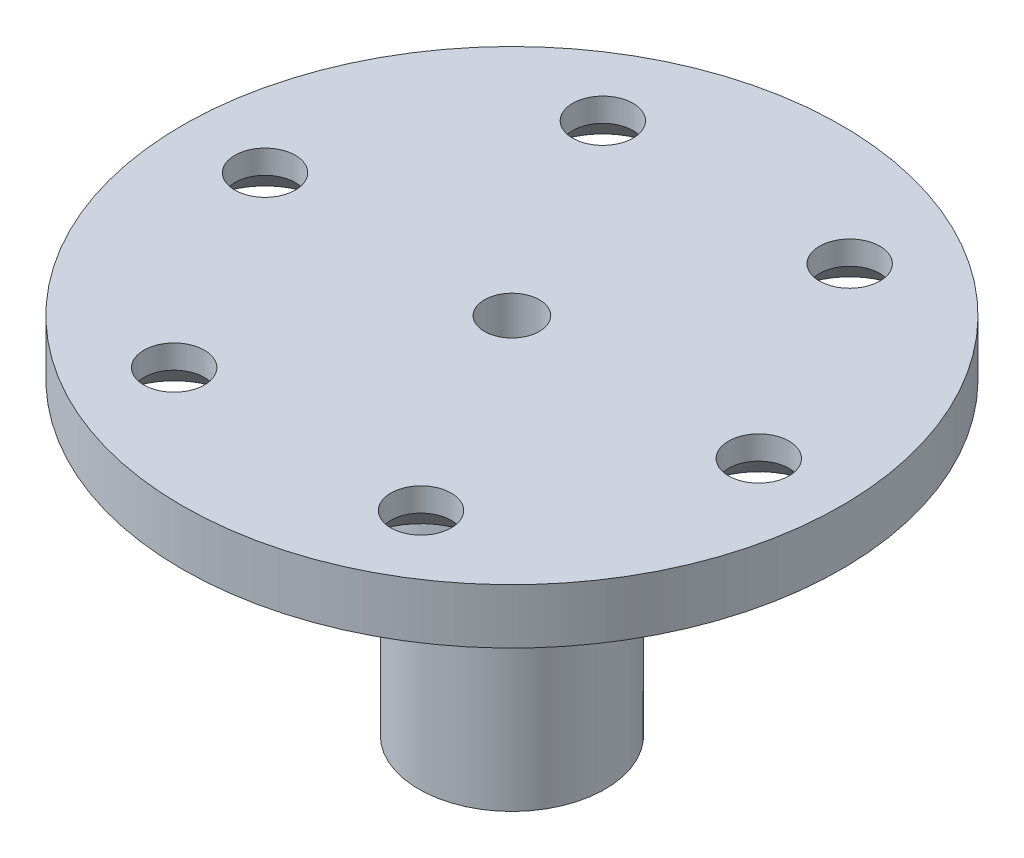
SolidWorks part; units mm, degrees
ref_plane "前视基准面" through (0, 0, 0) normal (0, 0, 1) x (1, 0, 0)
ref_plane "上视基准面" through (0, 0, 0) normal (0, 1, 0) x (1, 0, 0)
ref_plane "右视基准面" through (0, 0, 0) normal (1, 0, 0) x (0, 0, -1)
sketch "草图1" plane through (0, 0, 0) normal (0, 1, 0) x (1, 0, 0)
  circle A0 centre (0, 0) radius 8.475
  dimension "D1" = 16.95
extrude "凸台-拉伸1" add sketch "草图1" along normal blind 24.1
sketch "草图3" plane through (0, 0, 0) normal (0, -1, 0) x (1, 0, 0)
  circle A0 centre (0, 0) radius 5
  dimension "D1" = 10
extrude "切除-拉伸2" cut sketch "草图3" against normal up to next
sketch "草图4" plane through (0, 0, 0) normal (0, -1, 0) x (1, 0, 0)
  line L0 (-3.9472, 3.0691) -> (-4.0509, -2.9309)
  circle A0 centre (0, 0) radius 5 construction
  arc A1 (-4.0509, -2.9309) -> (-3.9472, 3.0691) centre (0, 0) cw
  dimension "D1" = 6
extrude "凸台-拉伸2" add sketch "草图4" against normal blind 22
ref_plane "基准面4" through (-7.9985, 0, 0.1382) normal (0.9999, 0, -0.0173) x (-0.0173, 0, -0.9999)
sketch "草图5" plane through (-7.9985, 0, 0.1382) normal (0.9999, 0, -0.0173) x (-0.0173, 0, -0.9999)
  line L0 (0, 0) -> (0, 21.0134) construction
  line L1 (-8.475, 0) -> (8.475, 0) construction
  circle A0 centre (0, 10) radius 1.6
  point P6 (0, 10)
  dimension "D2" = 3.2
  dimension "D4" = 10
sketch "草图6" plane through (0, 24.1, 0) normal (0, 1, 0) x (1, 0, 0)
  circle A0 centre (0, 0) radius 7.5
  circle A1 centre (0, 0) radius 12.5
  dimension "D1" = 25
extrude "凸台-拉伸3" add sketch "草图6" against normal blind 3
sketch "草图12" plane through (0, 24.1, 0) normal (0, 1, 0) x (1, 0, 0)
  line L0 (-4.0509, 2.9309) -> (-3.9472, -3.0691) construction
  line L1 (-5.0398, -9.0885) -> (10.3908, 0.1796)
  line L2 (10.3908, 0.1796) -> (-5.3509, 8.9089)
  line L3 (-5.3509, 8.9089) -> (-5.0398, -9.0885)
  circle A0 centre (0, 0) radius 5.1962 construction
  dimension "D1" = 18
hole_wizard "M3 螺纹孔3" [suppressed] positions "3D草图3" profile "草图13" tap size "M3" standard "GB"
sketch3d "3D草图3"
  point P0 (-5.3509, 24.1, -8.9089)
  point P3 (10.3908, 24.1, -0.1796)
  point P6 (-5.0398, 24.1, 9.0885)
sketch "草图13" plane through (-5.3509, 24.1, -8.9089) normal (1, 0, 0) x (0, 0, 1)
  line L0 (0, 0) -> (0, 24.1)
  line L1 (0, 24.1) -> (1.25, 24.1)
  line L2 (1.25, 24.1) -> (1.25, 0)
  line L5 (1.25, 0) -> (0, 0)
  line L11 (0, -6.35) -> (0, 107.95) construction
  dimension "通孔螺纹孔钻头直径" = 2.5
  dimension "通孔螺纹孔钻头深度" = 24.1
cosmetic thread "孔螺蚊线7" [suppressed] parameters "D2"=3
cosmetic thread "孔螺蚊线8" [suppressed] parameters "D2"=3
cosmetic thread "孔螺蚊线9" [suppressed] parameters "D2"=3
sketch "草图20" plane through (0, 21.1, 0) normal (0, -1, 0) x (1, 0, 0)
  circle A2 centre (0, 0) radius 8.475
  circle A3 centre (0, 0) radius 8.8
  dimension "D1" = 17.6
extrude "凸台-拉伸4" add sketch "草图20" along normal blind 1
sketch "草图21" plane through (-3.9991, 0, 0.0691) normal (0.9999, 0, -0.0173) x (-0.0173, 0, -0.9999)
  line L0 (3.0004, 0) -> (-3.0004, 0) construction
  line L1 (-3.0004, 22) -> (-3.0004, 0) construction
  circle A0 centre (0, 10) radius 1.6
  dimension "D1" = 3.2
  dimension "D2" = 10
hole_wizard "M3 螺纹孔4" positions "草图22" profile "草图23" tap size "M3" standard "GB"
sketch "草图22" plane through (-3.9991, 0, 0.0691) normal (0.9999, 0, -0.0173) x (-0.0173, 0, -0.9999)
  point P0 (0, 10)
sketch "草图23" plane through (-3.9991, 10, 0.0691) normal (0, 1, 0) x (-0.0173, 0, -0.9999)
  line L0 (0, 0) -> (0, 9.2511)
  line L1 (0, 9.2511) -> (1.25, 8.5)
  line L2 (1.25, 8.5) -> (1.25, 0)
  line L5 (1.25, 0) -> (0, 0)
  line L10 (0, 9.2511) -> (-1.25, 8.5) construction
  line L11 (0, -6.35) -> (0, 107.95) construction
  dimension "螺纹孔钻头直径" = 2.5
  dimension "螺纹孔钻头深度" = 8.5
  dimension "导头角度" = 118
cosmetic thread "孔螺蚊线10" parameters "D1"=4.4753, "D2"=3
sketch "草图24" plane through (0, 24.1, 0) normal (0, 1, 0) x (1, 0, 0)
  circle A0 centre (0, 0) radius 30
  dimension "D1" = 60
extrude "凸台-拉伸5" add sketch "草图24" along normal blind 5
sketch "草图25" plane through (0, 29.1, 0) normal (0, 1, 0) x (1, 0, 0)
  line L1 (-11.2756, -19.4708) -> (11.2244, -19.5003)
  line L2 (11.2244, -19.5003) -> (22.5, -0.0296)
  line L3 (22.5, -0.0296) -> (11.2756, 19.4708)
  line L4 (11.2756, 19.4708) -> (-11.2244, 19.5003)
  line L5 (-11.2244, 19.5003) -> (-22.5, 0.0296)
  line L6 (-22.5, 0.0296) -> (-11.2756, -19.4708)
  circle A0 centre (0, 0) radius 2.5
  circle A1 centre (0, 0) radius 19.4856 construction
  dimension "D1" = 5
  dimension "D2" = 22.5
extrude "切除-拉伸3" cut sketch "草图25" against normal blind 10 contours A0
hole_wizard "打孔尺寸(%根据十字)槽半沉头木螺钉的类型1" positions "草图30" profile "草图31" countersink size "M5" standard "GB" end condition through all
sketch "草图30" plane through (0, 24.1, 0) normal (0, -1, 0) x (-1, 0, 0)
  point P0 (11.2756, -19.4708)
  point P3 (-11.2244, -19.5003)
  point P6 (-22.5, -0.0296)
  point P9 (-11.2756, 19.4708)
  point P12 (11.2244, 19.5003)
  point P15 (22.5, 0.0296)
sketch "草图31" plane through (-11.2756, 24.1, 19.4708) normal (1, 0, 0) x (0, 0, -1)
  line L0 (0, 0) -> (0, 5)
  line L1 (0, 5) -> (2.75, 5)
  line L2 (2.75, 5) -> (2.75, 2.85)
  line L3 (2.75, 2.85) -> (5.6, 0)
  line L5 (5.6, 0) -> (0, 0)
  line L6 (-2.75, 2.85) -> (-5.6, 0) construction
  line L11 (0, -6.35) -> (0, 107.95) construction
  dimension "通孔孔直径" = 5.5
  dimension "通孔孔深度" = 5
  dimension "近端锥形沉头孔直径" = 11.2
  dimension "近端锥形沉头孔角度" = 90
ref_plane "基准面5" through (0, 0, 0) normal (0, -1, 0) x (-1, 0, 0)
sketch "草图34" plane through (0, 0, 0) normal (0, -1, 0) x (-1, 0, 0)
  circle A0 centre (0, 0) radius 5
  circle A1 centre (0, 0) radius 8.475
extrude "凸台-拉伸8" add sketch "草图34" along normal blind 4
